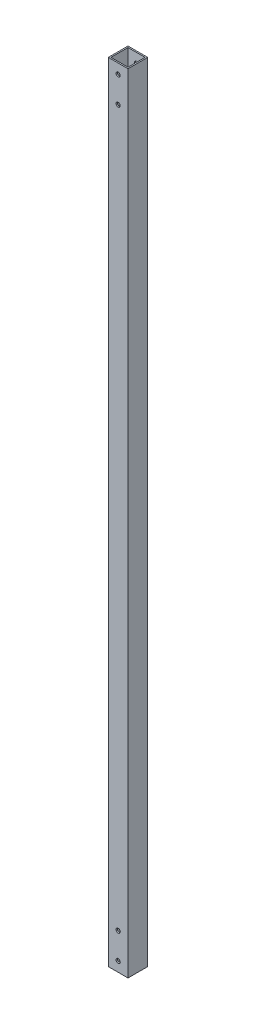
SolidWorks part; units mm, degrees
ref_plane "前视基准面" through (0, 0, 0) normal (0, 0, 1) x (1, 0, 0)
ref_plane "上视基准面" through (0, 0, 0) normal (0, 1, 0) x (1, 0, 0)
ref_plane "右视基准面" through (0, 0, 0) normal (1, 0, 0) x (0, 0, -1)
sketch "草图1" plane through (0, 0, 0) normal (0, 1, 0) x (1, 0, 0)
  line L1 (-7.5, -7.5) -> (7.5, -7.5)
  line L2 (-7.5, -7.5) -> (-7.5, 7.5)
  line L3 (-7.5, 7.5) -> (7.5, 7.5)
  line L4 (7.5, -7.5) -> (7.5, 7.5)
  line L5 (-7.5, -7.5) -> (7.5, 7.5) construction
  line L6 (-7.5, 7.5) -> (7.5, -7.5) construction
  point P0 (0, 0)
  dimension "D1" = 15
  dimension "D2" = 15
extrude "拉伸-薄壁1" add sketch "草图1" along normal blind 600 thin thin type one direction reverse wall 1
sketch "草图2" plane through (0, 0, 7.5) normal (0, 0, 1) x (1, 0, 0)
  line L0 (0, 0) -> (0, 600) construction
  line L1 (-7.5, 600) -> (7.5, 600) construction
  line L2 (-7.5, 0) -> (7.5, 0) construction
  circle A0 centre (0, 7.5) radius 1.6
  circle A1 centre (0, 27.5) radius 1.6
  circle A2 centre (0, 572.5) radius 1.6
  circle A3 centre (0, 592.5) radius 1.6
  dimension "D1" = 3.2
  dimension "D2" = 7.5
  dimension "D3" = 20
  dimension "D4" = 565
  dimension "D5" = 20
extrude "切除-拉伸1" cut sketch "草图2" against normal through all
